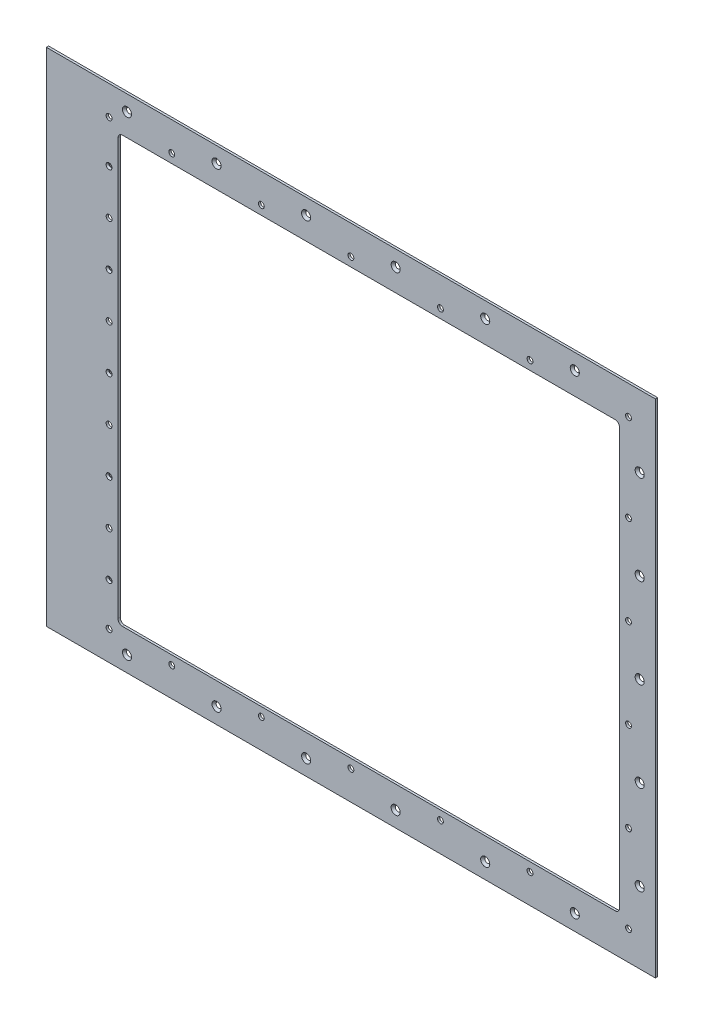
SolidWorks part; units mm, degrees
material "6061-T6 (SS)"
ref_plane "Front" through (0, 0, 0) normal (0, 0, 1) x (1, 0, 0)
ref_plane "Top" through (0, 0, 0) normal (0, 1, 0) x (1, 0, 0)
ref_plane "Right" through (0, 0, 0) normal (1, 0, 0) x (0, 0, -1)
sketch "Sketch2" plane through (0, 0, 0) normal (0, 0, 1) x (1, 0, 0)
  line L1 (0, 0) -> (863.6, 0)
  line L2 (0, 0) -> (0, 711.2)
  line L3 (0, 711.2) -> (863.6, 711.2)
  line L4 (863.6, 0) -> (863.6, 711.2)
  dimension "D1" = 863.6
  dimension "D2" = 711.2
extrude "Boss-Extrude1" add sketch "Sketch2" along normal blind 3.175
sketch "Sketch3" plane through (0, 0, 3.175) normal (0, 0, 1) x (1, 0, 0)
  line L0 (0, 711.2) -> (0, 0) construction
  line L1 (101.6, 53.975) -> (812.8, 53.975)
  line L2 (101.6, 53.975) -> (101.6, 657.225)
  line L3 (101.6, 657.225) -> (812.8, 657.225)
  line L4 (812.8, 53.975) -> (812.8, 657.225)
  line L5 (863.6, 0) -> (863.6, 711.2) construction
  line L6 (0, 0) -> (863.6, 0) construction
  line L7 (863.6, 711.2) -> (0, 711.2) construction
  dimension "D1" = 101.6
  dimension "D2" = 50.8
  dimension "D3" = 53.975
  dimension "D4" = 53.975
extrude "Cut-Extrude2" cut sketch "Sketch3" against normal through all
hole_wizard "CSK for 1/4 Flat Head Machine Screw1" positions "Sketch4" profile "Sketch5" countersink size "1/4" standard "ANSI Inch" end condition up to next
sketch "Sketch4" plane through (0, 0, 3.175) normal (0, 0, 1) x (1, 0, 0)
  line L0 (0, 0) -> (863.6, 0) construction
  line L1 (0, 711.2) -> (0, 0) construction
  point P0 (114.3, 22.225)
  dimension "D1" = 22.225
  dimension "D2" = 114.3
sketch "Sketch5" plane through (114.3, 22.225, 3.175) normal (1, 0, 0) x (0, -1, 0)
  line L0 (0, 0) -> (0, 3.175)
  line L1 (0, 3.175) -> (3.5712, 3.175)
  line L2 (3.5712, 3.175) -> (3.5712, 3.2989)
  line L3 (3.5712, 3.2989) -> (6.4389, 0)
  line L5 (6.4389, 0) -> (0, 0)
  line L6 (-3.5712, 3.2989) -> (-6.4389, 0) construction
  line L11 (0, -6.35) -> (0, 107.95) construction
  dimension "Thru Hole Dia." = 7.1425
  dimension "Thru Hole Depth" = 3.175
  dimension "Near C'Sink Dia." = 12.8778
  dimension "Near C'Sink Angle" = 82
pattern_linear "LPattern1" count 6 spacing 127 along (1, 0, 0) count 2 spacing 666.75 along (0, 1, 0) of "CSK for 1/4 Flat Head Machine Screw1"
hole_wizard "CSK for 1/4 Flat Head Machine Screw2" positions "Sketch6" profile "Sketch7" countersink size "1/4" standard "ANSI Inch" end condition up to next
sketch "Sketch6" plane through (0, 0, 3.175) normal (0, 0, 1) x (1, 0, 0)
  line L0 (863.6, 0) -> (863.6, 711.2) construction
  line L1 (0, 0) -> (863.6, 0) construction
  point P0 (841.375, 101.6)
  dimension "D1" = 22.225
  dimension "D2" = 101.6
sketch "Sketch7" plane through (841.375, 101.6, 3.175) normal (1, 0, 0) x (0, -1, 0)
  line L0 (0, 0) -> (0, 3.175)
  line L1 (0, 3.175) -> (3.5712, 3.175)
  line L2 (3.5712, 3.175) -> (3.5712, 3.2989)
  line L3 (3.5712, 3.2989) -> (6.4389, 0)
  line L5 (6.4389, 0) -> (0, 0)
  line L6 (-3.5712, 3.2989) -> (-6.4389, 0) construction
  line L11 (0, -6.35) -> (0, 107.95) construction
  dimension "Thru Hole Dia." = 7.1425
  dimension "Thru Hole Depth" = 3.175
  dimension "Near C'Sink Dia." = 12.8778
  dimension "Near C'Sink Angle" = 82
pattern_linear "LPattern2" count 5 spacing 127 along (0, 1, 0) of "CSK for 1/4 Flat Head Machine Screw2"
fillet "Fillet1" radius 6.35 4 edges at (101.6, 53.975, 1.5875) (812.8, 53.975, 1.5875) (812.8, 657.225, 1.5875) (101.6, 657.225, 1.5875)
hole_wizard "21/64 (0.32813) Diameter Hole1" positions "Sketch10" profile "Sketch11" hole size "21/64" standard "ANSI Inch" end condition through all
sketch "Sketch10" plane through (0, 0, 3.175) normal (0, 0, 1) x (1, 0, 0)
  line L0 (812.8, 60.325) -> (812.8, 650.875) construction
  line L1 (107.95, 53.975) -> (806.45, 53.975) construction
  point P0 (825.5, 41.275)
  dimension "D1" = 12.7
  dimension "D2" = 12.7
sketch "Sketch11" plane through (825.5, 41.275, 3.175) normal (1, 0, 0) x (0, -1, 0)
  line L0 (0, 0) -> (0, 3.175)
  line L1 (0, 3.175) -> (4.1673, 3.175)
  line L2 (4.1673, 3.175) -> (4.1673, 0)
  line L5 (4.1673, 0) -> (0, 0)
  line L11 (0, -6.35) -> (0, 107.95) construction
  dimension "Thru Hole Dia." = 8.3345
  dimension "Thru Hole Depth" = 3.175
pattern_linear "LPattern4" count 2 spacing 736.6 along (-1, 0, 0) count 2 spacing 628.65 along (0, 1, 0) of "21/64 (0.32813) Diameter Hole1"
hole_wizard "21/64 (0.32813) Diameter Hole2" positions "Sketch12" profile "Sketch13" hole size "21/64" standard "ANSI Inch" end condition through all
sketch "Sketch12" plane through (0, 0, 3.175) normal (0, 0, 1) x (1, 0, 0)
  line L0 (107.95, 53.975) -> (806.45, 53.975) construction
  circle A0 centre (825.5, 41.275) radius 4.1673 construction
  point P0 (685.8, 41.275)
  dimension "D2" = 139.7
  dimension "D1" = 12.7
sketch "Sketch13" plane through (685.8, 41.275, 3.175) normal (1, 0, 0) x (0, -1, 0)
  line L0 (0, 0) -> (0, 3.175)
  line L1 (0, 3.175) -> (4.1673, 3.175)
  line L2 (4.1673, 3.175) -> (4.1673, 0)
  line L5 (4.1673, 0) -> (0, 0)
  line L11 (0, -6.35) -> (0, 107.95) construction
  dimension "Thru Hole Dia." = 8.3345
  dimension "Thru Hole Depth" = 3.175
pattern_linear "LPattern5" count 5 spacing 127 along (-1, 0, 0) count 2 spacing 628.65 along (0, 1, 0) of "21/64 (0.32813) Diameter Hole2"
hole_wizard "21/64 (0.32813) Diameter Hole3" positions "Sketch14" profile "Sketch15" hole size "21/64" standard "ANSI Inch" end condition through all
sketch "Sketch14" plane through (0, 0, 3.175) normal (0, 0, 1) x (1, 0, 0)
  line L0 (812.8, 60.325) -> (812.8, 650.875) construction
  circle A0 centre (825.5, 41.275) radius 4.1673 construction
  point P0 (825.5, 165.1)
  dimension "D2" = 123.825
  dimension "D1" = 12.7
sketch "Sketch15" plane through (825.5, 165.1, 3.175) normal (1, 0, 0) x (0, -1, 0)
  line L0 (0, 0) -> (0, 3.175)
  line L1 (0, 3.175) -> (4.1673, 3.175)
  line L2 (4.1673, 3.175) -> (4.1673, 0)
  line L5 (4.1673, 0) -> (0, 0)
  line L11 (0, -6.35) -> (0, 107.95) construction
  dimension "Thru Hole Dia." = 8.3345
  dimension "Thru Hole Depth" = 3.175
pattern_linear "LPattern6" count 4 spacing 127 along (0, 1, 0) count 2 spacing 736.6 along (-1, 0, 0) of "21/64 (0.32813) Diameter Hole3"
hole_wizard "CSK for #8 Flat Head Machine Screw1" positions "Sketch16" profile "Sketch17" countersink size "#8" standard "ANSI Inch" end condition through all
sketch "Sketch16" plane through (0, 0, 3.175) normal (0, 0, 1) x (1, 0, 0)
  line L0 (101.6, 650.875) -> (101.6, 60.325) construction
  circle A0 centre (88.9, 546.1) radius 4.1673 construction
  point P0 (88.9, 609.6)
  dimension "D1" = 12.7
  dimension "D2" = 63.5
sketch "Sketch17" plane through (88.9, 609.6, 3.175) normal (1, 0, 0) x (0, -1, 0)
  line L0 (0, 0) -> (0, 3.175)
  line L1 (0, 3.175) -> (2.2479, 3.175)
  line L2 (2.2479, 3.175) -> (2.2479, 2.2645)
  line L3 (2.2479, 2.2645) -> (4.2164, 0)
  line L5 (4.2164, 0) -> (0, 0)
  line L6 (-2.2479, 2.2645) -> (-4.2164, 0) construction
  line L11 (0, -6.35) -> (0, 107.95) construction
  dimension "Thru Hole Dia." = 4.4958
  dimension "Thru Hole Depth" = 3.175
  dimension "Near C'Sink Dia." = 8.4328
  dimension "Near C'Sink Angle" = 82
pattern_linear "LPattern7" count 5 spacing 127 along (0, -1, 0) of "CSK for #8 Flat Head Machine Screw1"
